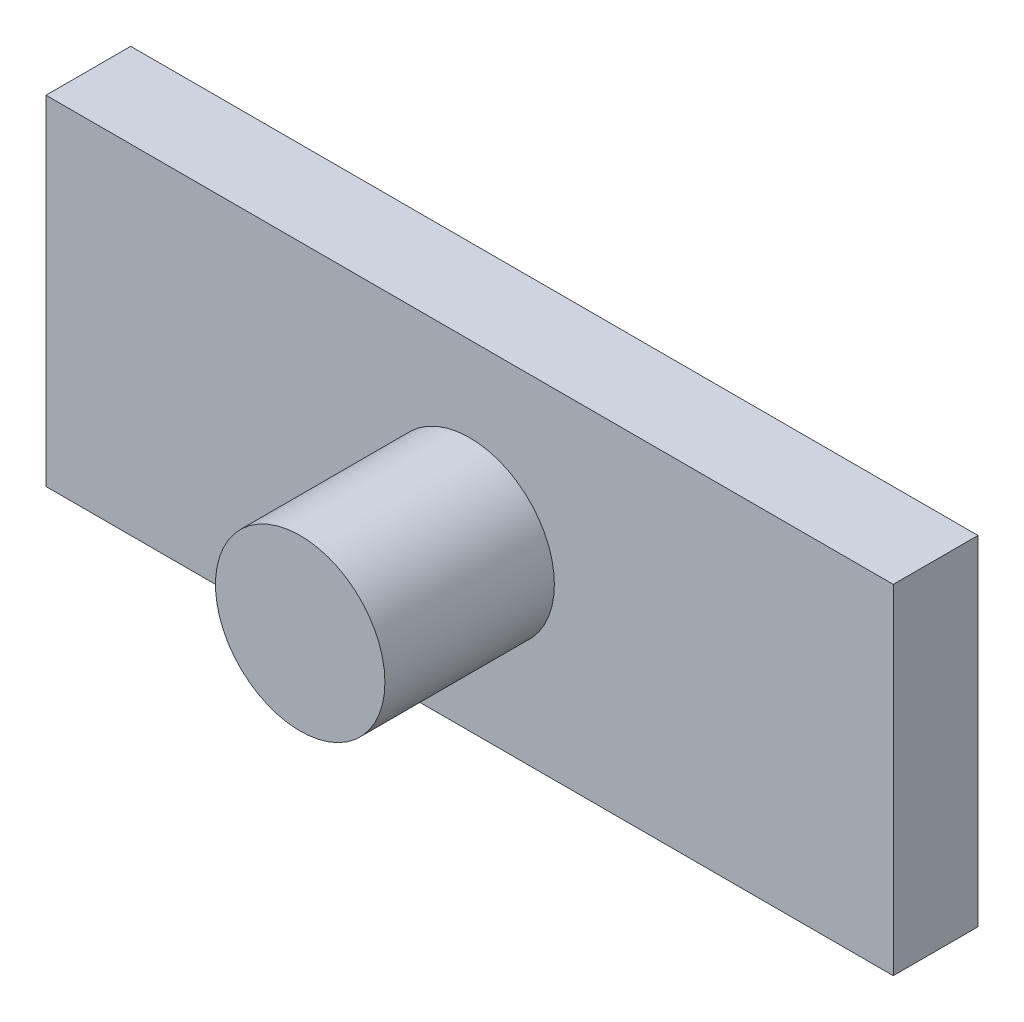
SolidWorks part; units mm, degrees
ref_plane "前视基准面" through (0, 0, 0) normal (0, 0, 1) x (1, 0, 0)
ref_plane "上视基准面" through (0, 0, 0) normal (0, 1, 0) x (1, 0, 0)
ref_plane "右视基准面" through (0, 0, 0) normal (1, 0, 0) x (0, 0, -1)
sketch "草图2" plane through (0, 0, 0) normal (0, 0, 1) x (1, 0, 0)
  line L1 (-50, 20) -> (50, 20)
  line L2 (-50, 20) -> (-50, -20)
  line L3 (-50, -20) -> (50, -20)
  line L4 (50, 20) -> (50, -20)
  line L5 (0, -20) -> (0, 20) construction
  line L6 (-50, 0) -> (50, 0) construction
  point P0 (0, 0)
  dimension "D1" = 100
  dimension "D2" = 40
extrude "凸台-拉伸1" add sketch "草图2" along normal blind 10
sketch "草图3" plane through (0, 0, 10) normal (0, 0, 1) x (1, 0, 0)
  circle A0 centre (0, 0) radius 10
  dimension "D1" = 20
extrude "凸台-拉伸2" add sketch "草图3" along normal blind 20
